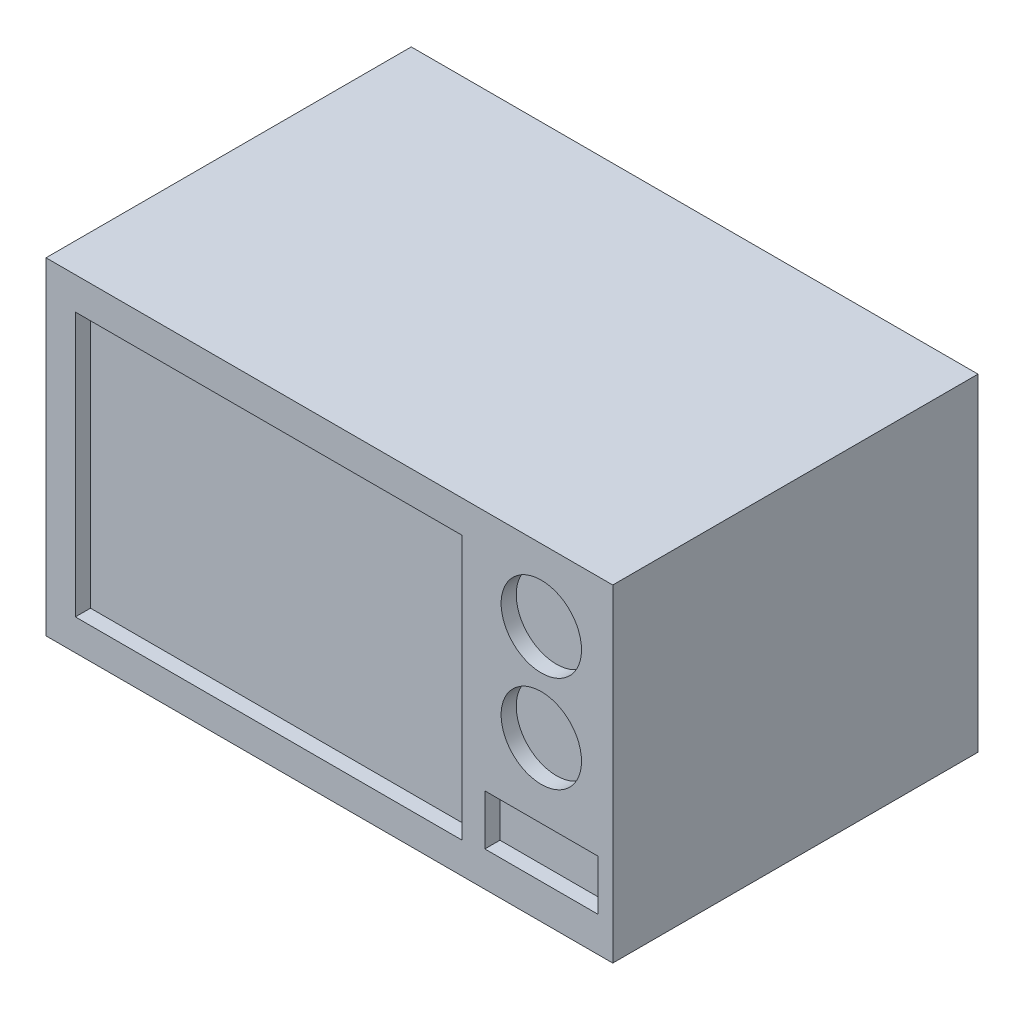
SolidWorks part; units mm, degrees
ref_plane "Front Plane" through (0, 0, 0) normal (0, 0, 1) x (1, 0, 0)
ref_plane "Top Plane" through (0, 0, 0) normal (0, 1, 0) x (1, 0, 0)
ref_plane "Right Plane" through (0, 0, 0) normal (1, 0, 0) x (0, 0, -1)
sketch "Sketch1" plane through (0, 0, 0) normal (0, 1, 0) x (1, 0, 0)
  line L1 (-225, 145) -> (225, 145)
  line L2 (-225, 145) -> (-225, -145)
  line L3 (-225, -145) -> (225, -145)
  line L4 (225, 145) -> (225, -145)
  line L5 (-225, 145) -> (225, -145) construction
  line L6 (-225, -145) -> (225, 145) construction
  point P0 (0, 0)
  dimension "D1" = 450
  dimension "D2" = 290
extrude "Boss-Extrude1" add sketch "Sketch1" along normal blind 260
sketch "Sketch2" plane through (0, 0, 145) normal (0, 0, 1) x (1, 0, 0)
  line L1 (123.4331, 67.6836) -> (213.1187, 67.6836)
  line L2 (123.4331, 67.6836) -> (123.4331, 27.7112)
  line L3 (123.4331, 27.7112) -> (213.1187, 27.7112)
  line L4 (213.1187, 67.6836) -> (213.1187, 27.7112)
  line L5 (123.4331, 67.6836) -> (213.1187, 27.7112) construction
  line L6 (123.4331, 27.7112) -> (213.1187, 67.6836) construction
  line L7 (-201.677, 234.3497) -> (105.3107, 234.3497)
  line L8 (-201.677, 234.3497) -> (-201.677, 24.7169)
  line L9 (-201.677, 24.7169) -> (105.3107, 24.7169)
  line L10 (105.3107, 234.3497) -> (105.3107, 24.7169)
  line L11 (-201.677, 234.3497) -> (105.3107, 24.7169) construction
  line L12 (-201.677, 24.7169) -> (105.3107, 234.3497) construction
  circle A0 centre (168.2759, 203.0666) radius 31.9153
  circle A1 centre (168.2759, 126.4183) radius 31.9153
  point P4 (96.0727, 230.7966)
  point P5 (168.2759, 47.6974)
  point P13 (-48.1831, 129.5333)
extrude "Cut-Extrude1" cut sketch "Sketch2" against normal blind 12
